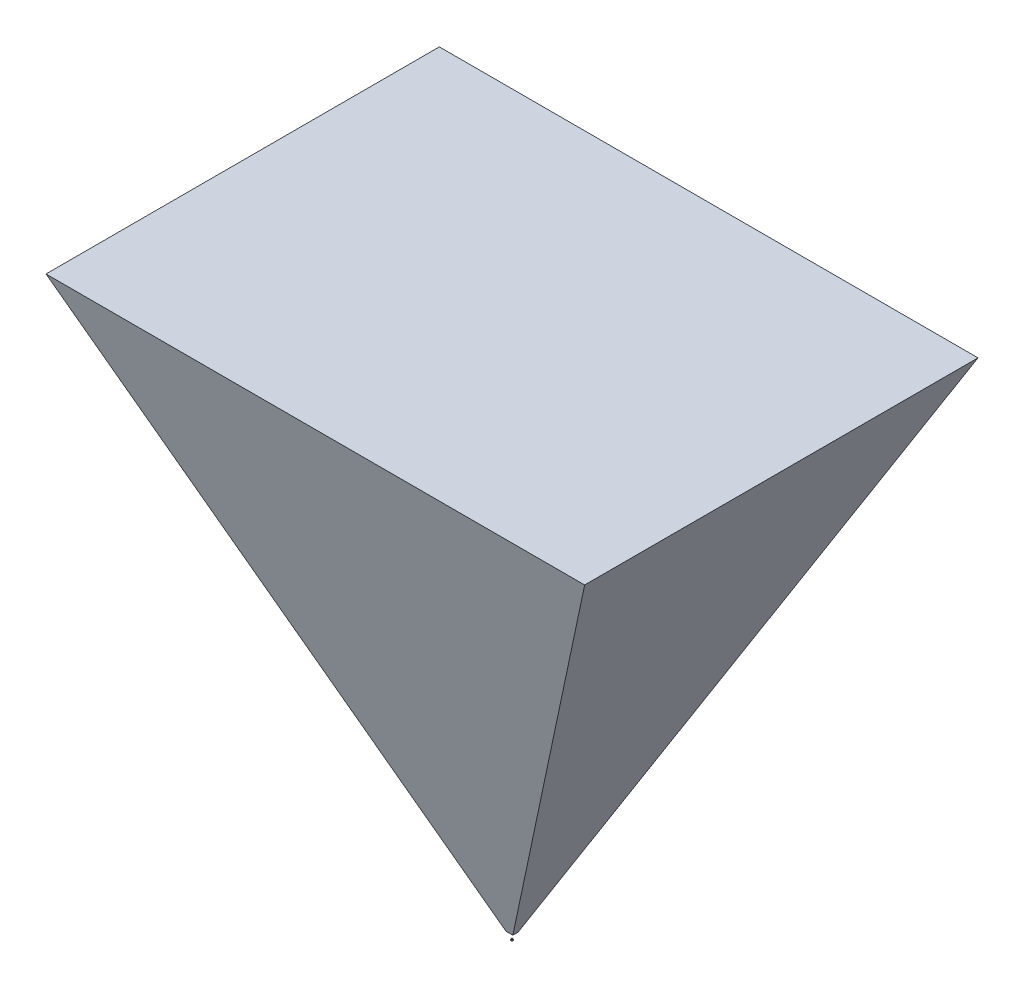
SolidWorks part; units mm, degrees
material "ABS PC"
ref_plane "Vorne" through (0, 0, 0) normal (0, 0, 1) x (1, 0, 0)
ref_plane "Oben" through (0, 0, 0) normal (0, 1, 0) x (1, 0, 0)
ref_plane "Rechts" through (0, 0, 0) normal (1, 0, 0) x (0, 0, -1)
sketch "Skizze3" plane through (0, 0, 0) normal (0, 0, 1) x (1, 0, 0)
  line L0 (0, 0) -> (0, -2.1568) construction
  line L1 (1, 0.8) -> (2.75, 0.8)
  line L2 (2.75, 0.8) -> (2.75, -2.55)
  line L3 (2.75, -2.55) -> (2.1, -2.55)
  line L4 (1, 0.8) -> (0.625, 0.425)
  line L5 (0.8125, 0.6125) -> (0.8125, 0.8) construction
  line L6 (0.8125, 0.8) -> (1, 0.8) construction
  line L7 (2.1, -2.55) -> (1.8, -2.25)
  line L8 (2.1, -2.55) -> (2.1, -2.4) construction
  line L9 (2.1, -2.4) -> (1.95, -2.4) construction
  line L10 (0, -2.55) -> (0, 0.525)
  arc A0 (1.8, -2.25) -> (0, -2.55) centre (0, 3) cw
  arc A1 (0, 0.525) -> (0.625, 0.425) centre (0, -1.4781) cw
  dimension "D6" = 0.1
  dimension "D1" = 3.35
  dimension "D2" = 5.5
  dimension "D3" = 2
  dimension "D4" = 1.25
  dimension "D5" = 3.6
  dimension "D7" = 0.8
  dimension "D8" = 0.3
revolve "Body" add sketch "Skizze3" angle 360 about L0
sketch "Skizze4" plane through (0, 0, 0) normal (0, 0, 1) x (1, 0, 0)
  line L0 (0, 0) -> (0, 1.3093) construction
  line L1 (2.75, -2.55) -> (2.75, 0.8) construction
  line L2 (2.75, -0.2) -> (3, -0.2)
  line L3 (2.75, -0.2) -> (2.75, -1.2)
  line L4 (2.75, -1.2) -> (3, -1.2)
  line L5 (3, -0.2) -> (3, -1.2)
  line L6 (2.75, 0.8) -> (-2.75, 0.8) construction
  dimension "D1" = 2
  dimension "D2" = 1
  dimension "D3" = 6
revolve "Thread" add sketch "Skizze4" angle 360 about L0
sketch "Skizze5" plane through (0, 0, 0) normal (1, 0, 0) x (0, 0, -1)
  line L0 (0, 0) -> (0, -3.7681) construction
  line L1 (2.75, 0.8) -> (2.75, 0.35)
  line L2 (2.75, -0.2) -> (2.75, 0.8) construction
  line L3 (2.75, 0.35) -> (2.3, 0.8)
  line L4 (2.75, 0.8) -> (-2.75, 0.8) construction
  line L5 (2.3, 0.8) -> (2.75, 0.8)
  dimension "D1" = 0.45
revolve "Toolface" cut sketch "Skizze5" angle 60 about L0
pattern_circular "Kreismuster1" count 3 over 360 about axis through (0, 0, 0) along (0, 1, 0) of "Toolface"
sketch "Skizze6" plane through (0, 0, 0) normal (1, 0, 0) x (0, 0, -1)
  line L0 (0, 0) -> (0, 10.2784) construction
  line L1 (-7.2794, 18.7078) -> (-564.1539, 1548.7078)
  line L2 (-564.1539, 1548.7078) -> (564.1539, 1548.7078)
  line L3 (-7.2794, 18.7078) -> (7.2794, 18.7078)
  line L4 (0, 1548.7078) -> (0, 18.7078) construction
  line L5 (-7.2794, 18.7078) -> (0, -1.2922) construction
  line L8 (7.2794, 18.7078) -> (564.1539, 1548.7078)
  point P3 (-0.625, 0.425)
  dimension "D1" = 1530
  dimension "D2" = 20
  dimension "D3" = 40
extrude "FOV - 3,6mm f/2,9" add sketch "Skizze6" along normal mid plane 3000 separate body
sketch "Skizze8" plane through (0, 0, 0) normal (0, 0, 1) x (1, 0, 0)
  line L0 (0, 0) -> (0, 233.3089) construction
  line L1 (-9.7405, 18.7078) -> (-772.5703, 1548.7078)
  line L2 (1500, 18.7078) -> (-1500, 18.7078) construction
  line L3 (1500, 1548.7078) -> (-1500, 1548.7078) construction
  line L4 (-772.5703, 1548.7078) -> (772.5703, 1548.7078)
  line L5 (-9.7405, 18.7078) -> (9.7405, 18.7078)
  line L8 (9.7405, 18.7078) -> (772.5703, 1548.7078)
  circle A0 centre (0, 0) radius 5
  point P9 (-0.625, 0.425)
  point P16 (0, 18.7078)
  point P17 (0, 1548.7078)
  dimension "D2" = 10
  dimension "D1" = 53
extrude "FOV2" cut sketch "Skizze8" against normal through all and the other way through all flip side to cut
